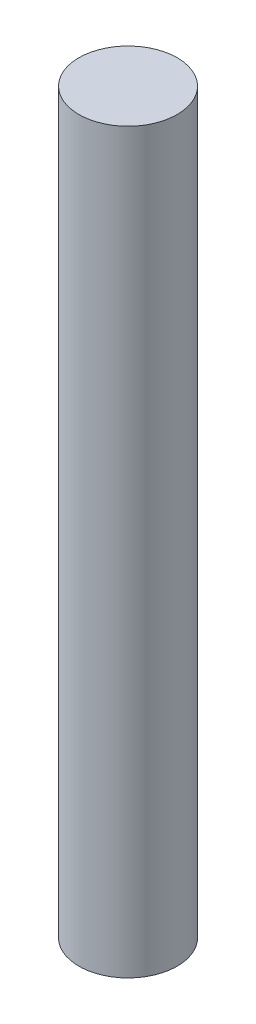
SolidWorks part; units mm, degrees
ref_plane "Front Plane" through (0, 0, 0) normal (0, 0, 1) x (1, 0, 0)
ref_plane "Top Plane" through (0, 0, 0) normal (0, 1, 0) x (1, 0, 0)
ref_plane "Right Plane" through (0, 0, 0) normal (1, 0, 0) x (0, 0, -1)
sketch "Sketch1" plane through (0, 0, 0) normal (0, 1, 0) x (1, 0, 0)
  circle A0 centre (0, 0) radius 1.5
  dimension "D1" = 3
extrude "Boss-Extrude1" add sketch "Sketch1" along normal mid plane 22.5
